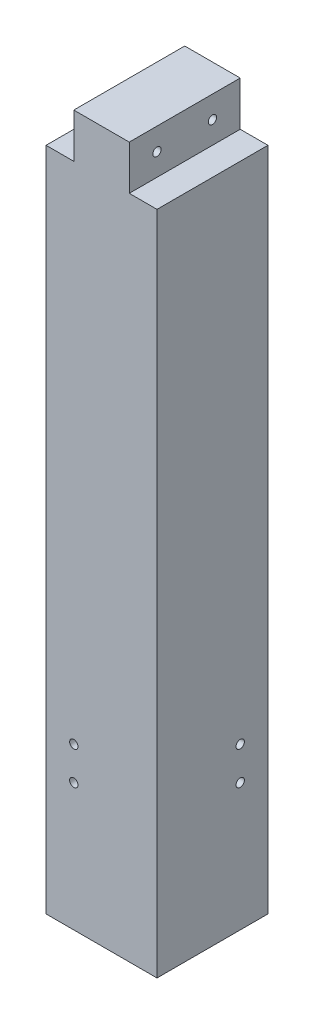
SolidWorks part; units mm, degrees
material "Pine"
ref_plane "Front Plane" through (0, 0, 0) normal (0, 0, 1) x (1, 0, 0)
ref_plane "Top Plane" through (0, 0, 0) normal (0, 1, 0) x (1, 0, 0)
ref_plane "Right Plane" through (0, 0, 0) normal (1, 0, 0) x (0, 0, -1)
sketch "Sketch1" plane through (0, 0, 0) normal (0, 0, 1) x (1, 0, 0)
  line L1 (63.5, 381) -> (-63.5, 381)
  line L2 (63.5, 381) -> (63.5, -381)
  line L3 (63.5, -381) -> (-63.5, -381)
  line L4 (-63.5, 381) -> (-63.5, -381)
  line L5 (63.5, 381) -> (-63.5, -381) construction
  line L6 (63.5, -381) -> (-63.5, 381) construction
  line L7 (31.75, 431.8) -> (-31.75, 431.8)
  line L8 (31.75, 431.8) -> (31.75, 330.2)
  line L9 (31.75, 330.2) -> (-31.75, 330.2)
  line L10 (-31.75, 431.8) -> (-31.75, 330.2)
  line L11 (31.75, 431.8) -> (-31.75, 330.2) construction
  line L12 (31.75, 330.2) -> (-31.75, 431.8) construction
  line L13 (0, -177.8) -> (-31.75, -177.8)
  line L14 (0, -177.8) -> (0, -254)
  line L15 (0, -254) -> (-31.75, -254)
  line L16 (-31.75, -177.8) -> (-31.75, -254)
  line L17 (0, -177.8) -> (-31.75, -254) construction
  line L18 (0, -254) -> (-31.75, -177.8) construction
  point P0 (0, 0)
  point P6 (0, 381)
  point P11 (-15.875, -215.9)
  dimension "D1" = 762
  dimension "D2" = 127
  dimension "D3" = 101.6
  dimension "D4" = 63.5
  dimension "D5" = 31.75
  dimension "D6" = 127
  dimension "D7" = 76.2
  dimension "D8" = 31.75
extrude "Boss-Extrude1" add sketch "Sketch1" against normal blind 127 contours L7 L10 L1 L8
sketch "Sketch4" plane through (-63.5, 0, 0) normal (-1, 0, 0) x (0, 0, 1)
  line L1 (-31.75, -177.8) -> (-63.5, -177.8)
  line L2 (-31.75, -177.8) -> (-31.75, -254)
  line L3 (-31.75, -254) -> (-63.5, -254)
  line L4 (-63.5, -177.8) -> (-63.5, -254)
  line L5 (-31.75, -177.8) -> (-63.5, -254) construction
  line L6 (-31.75, -254) -> (-63.5, -177.8) construction
  line L7 (-127, -381) -> (0, -381) construction
  line L8 (0, 381) -> (0, -381) construction
  point P0 (-47.625, -215.9)
  dimension "D1" = 76.2
  dimension "D2" = 31.75
  dimension "D3" = 31.75
  dimension "D4" = 127
extrude "Cut-Extrude3" cut sketch "Sketch4" against normal blind 63.5
sketch "Sketch5" plane through (0, 0, -127) normal (0, 0, -1) x (-1, 0, 0)
  line L1 (0, -177.8) -> (-31.75, -177.8)
  line L2 (0, -177.8) -> (0, -254)
  line L3 (0, -254) -> (-31.75, -254)
  line L4 (-31.75, -177.8) -> (-31.75, -254)
  line L5 (0, -177.8) -> (-31.75, -254) construction
  line L6 (0, -254) -> (-31.75, -177.8) construction
  line L7 (-63.5, -381) -> (63.5, -381) construction
  line L8 (-63.5, 381) -> (-63.5, -381) construction
  point P0 (-15.875, -215.9)
  dimension "D1" = 76.2
  dimension "D2" = 31.75
  dimension "D3" = 31.75
  dimension "D4" = 127
extrude "Cut-Extrude4" cut sketch "Sketch5" against normal blind 63.246
sketch "Sketch7" plane through (63.5, 0, 0) normal (1, 0, 0) x (0, 0, -1)
  line L0 (95.25, -177.8) -> (95.25, -254) construction
  line L4 (127, -254) -> (127, -177.8)
  line L5 (63.754, -254) -> (127, -254)
  line L6 (63.754, -177.8) -> (63.754, -254)
  line L7 (127, -177.8) -> (63.754, -177.8)
  line L8 (127, -254) -> (127, -177.8)
  line L9 (63.754, -254) -> (127, -254)
  line L10 (63.754, -177.8) -> (63.754, -254)
  line L11 (127, -177.8) -> (63.754, -177.8)
  circle A0 centre (95.25, -234.95) radius 4.7625
  circle A1 centre (95.25, -196.85) radius 4.7625
  point P10 (95.25, -215.9)
  dimension "D2" = 9.525
  dimension "D3" = 19.05
  dimension "D4" = 19.05
  dimension "D5" = 31.75
  dimension "D1" = 0
extrude "Cut-Extrude6" cut sketch "Sketch7" against normal blind 69.85 contours A0 L0 | L0 A0 | A1 L0 | L0 A1
sketch "Sketch8" plane through (0, 0, 0) normal (0, 0, 1) x (1, 0, 0)
  line L0 (-31.75, -177.8) -> (-31.75, -254) construction
  line L4 (-63.5, -177.8) -> (-63.5, -254)
  line L5 (0, -177.8) -> (-63.5, -177.8)
  line L6 (0, -254) -> (0, -177.8)
  line L7 (-63.5, -254) -> (0, -254)
  line L8 (-63.5, -177.8) -> (-63.5, -254)
  line L9 (0, -177.8) -> (-63.5, -177.8)
  line L10 (0, -254) -> (0, -177.8)
  line L11 (-63.5, -254) -> (0, -254)
  circle A0 centre (-31.75, -234.95) radius 4.7625
  circle A1 centre (-31.75, -196.85) radius 4.7625
  point P10 (-31.75, -215.9)
  dimension "D2" = 9.525
  dimension "D3" = 19.05
  dimension "D4" = 19.05
  dimension "D5" = 31.75
  dimension "D1" = 0
extrude "Cut-Extrude8" cut sketch "Sketch8" against normal blind 69.85 contours A0 L0 | L0 A0 | L0 A1 | A1 L0
sketch "Sketch9" plane through (-31.75, 0, 0) normal (-1, 0, 0) x (0, 0, 1)
  line L0 (-127, 406.4) -> (0, 406.4) construction
  line L1 (-127, 431.8) -> (-127, 381) construction
  line L2 (0, 431.8) -> (0, 381) construction
  circle A0 centre (-95.25, 406.4) radius 4.7625
  circle A1 centre (-31.75, 406.4) radius 4.7625
  point P10 (-63.5, 406.4)
  dimension "D1" = 9.525
  dimension "D2" = 31.75
  dimension "D3" = 31.75
extrude "Cut-Extrude9" cut sketch "Sketch9" against normal through all
sketch "Sketch6" plane through (0, 0, 0) normal (0, 0, 1) x (1, 0, 0)
  line L0 (-31.75, -177.8) -> (-31.75, -254) construction
  line L4 (-63.5, -177.8) -> (-63.5, -254)
  line L5 (0, -177.8) -> (-63.5, -177.8)
  line L6 (0, -254) -> (0, -177.8)
  line L7 (-63.5, -254) -> (0, -254)
  line L8 (-63.5, -177.8) -> (-63.5, -254)
  line L9 (0, -177.8) -> (-63.5, -177.8)
  line L10 (0, -254) -> (0, -177.8)
  line L11 (-63.5, -254) -> (0, -254)
  circle A0 centre (-31.75, -196.85) radius 4.7625
  circle A1 centre (-31.75, -234.95) radius 4.7625
  point P10 (-31.75, -215.9)
  dimension "D2" = 9.525
  dimension "D3" = 19.05
  dimension "D4" = 19.05
  dimension "D1" = 0
